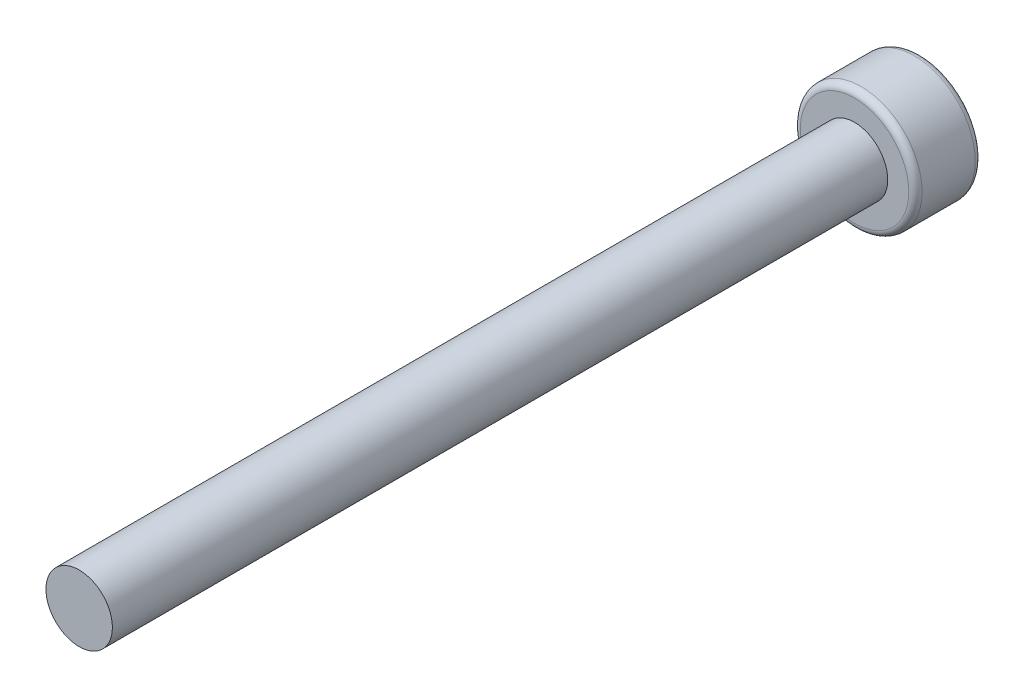
SolidWorks part; units mm, degrees
ref_plane "前视基准面" through (0, 0, 0) normal (0, 0, 1) x (1, 0, 0)
ref_plane "上视基准面" through (0, 0, 0) normal (0, 1, 0) x (1, 0, 0)
ref_plane "右视基准面" through (0, 0, 0) normal (1, 0, 0) x (0, 0, -1)
sketch "草图1" plane through (0, 0, 0) normal (0, 0, 1) x (1, 0, 0)
  circle A0 centre (0, 0) radius 2.75
  dimension "D1" = 2.75
extrude "凸台-拉伸1" add sketch "草图1" along normal blind 3
sketch "草图2" plane through (0, 0, 3) normal (0, 0, 1) x (1, 0, 0)
  circle A0 centre (0, 0) radius 1.5
  dimension "D1" = 1.5
extrude "凸台-拉伸2" add sketch "草图2" along normal blind 35
cosmetic thread "装饰螺纹线1" parameters "D2"=2
fillet "圆角1" radius 0.3 2 edges at (2.75, 0, 0) (2.75, 0, 3)
sketch "草图3" plane through (0, 0, 0) normal (0, 0, -1) x (-1, 0, 0)
  line L1 (-0.8209, 1.8624) -> (-2.0233, 0.2203)
  line L2 (-2.0233, 0.2203) -> (-1.2025, -1.6421)
  line L3 (-1.2025, -1.6421) -> (0.8209, -1.8624)
  line L4 (0.8209, -1.8624) -> (2.0233, -0.2203)
  line L5 (2.0233, -0.2203) -> (1.2025, 1.6421)
  line L6 (1.2025, 1.6421) -> (-0.8209, 1.8624)
  circle A0 centre (0, 0) radius 1.7626 construction
extrude "切除-拉伸1" cut sketch "草图3" against normal blind 2
